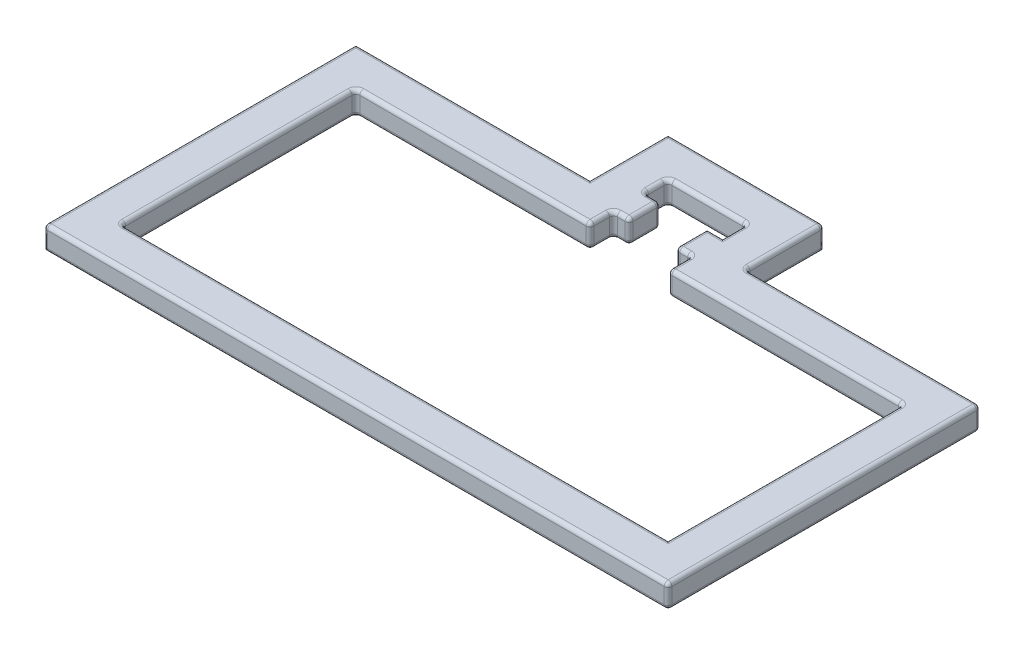
SolidWorks part; units mm, degrees
ref_plane "Front Plane" through (0, 0, 0) normal (0, 0, 1) x (1, 0, 0)
ref_plane "Top Plane" through (0, 0, 0) normal (0, 1, 0) x (1, 0, 0)
ref_plane "Right Plane" through (0, 0, 0) normal (1, 0, 0) x (0, 0, -1)
sketch "Sketch1" plane through (0, 0, 0) normal (0, 1, 0) x (1, 0, 0)
  line L1 (-84.8117, 120.1282) -> (-4.8117, 120.1282)
  line L2 (-84.8117, 120.1282) -> (-84.8117, 80.1282)
  line L3 (-84.8117, 80.1282) -> (-4.8117, 80.1282)
  line L4 (-4.8117, 120.1282) -> (-4.8117, 80.1282)
  line L5 (-79.8117, 115.1282) -> (-9.8117, 115.1282)
  line L6 (-79.8117, 115.1282) -> (-79.8117, 85.1282)
  line L7 (-79.8117, 85.1282) -> (-9.8117, 85.1282)
  line L8 (-9.8117, 115.1282) -> (-9.8117, 85.1282)
  line L17 (-49.8117, 125.1282) -> (-39.8117, 125.1282)
  line L18 (-54.8117, 130.1282) -> (-34.8117, 130.1282)
  line L19 (-54.8117, 130.1282) -> (-54.8117, 120.1282)
  line L20 (-54.8117, 120.1282) -> (-34.8117, 120.1282)
  line L21 (-34.8117, 130.1282) -> (-34.8117, 120.1282)
  line L22 (-49.8117, 125.1282) -> (-49.8117, 115.1282)
  line L23 (-49.8117, 115.1282) -> (-39.8117, 115.1282)
  line L24 (-39.8117, 125.1282) -> (-39.8117, 115.1282)
  line L25 (-49.8117, 118.1282) -> (-47.8117, 118.1282)
  line L26 (-49.8117, 118.1282) -> (-49.8117, 122.1282)
  line L27 (-49.8117, 122.1282) -> (-47.8117, 122.1282)
  line L28 (-47.8117, 118.1282) -> (-47.8117, 122.1282)
  line L29 (-39.8117, 118.1282) -> (-41.8117, 118.1282)
  line L30 (-39.8117, 118.1282) -> (-39.8117, 122.1282)
  line L31 (-39.8117, 122.1282) -> (-41.8117, 122.1282)
  line L32 (-41.8117, 118.1282) -> (-41.8117, 122.1282)
  dimension "D1" = 80
  dimension "D2" = 40
  dimension "D3" = 5
  dimension "D4" = 5
  dimension "D5" = 5
  dimension "D6" = 5
  dimension "D7" = 20
  dimension "D8" = 10
  dimension "D9" = 5
  dimension "D10" = 5
  dimension "D11" = 30
  dimension "D12" = 10
  dimension "D13" = 4
  dimension "D14" = 2
  dimension "D15" = 3
  dimension "D16" = 2
  dimension "D17" = 4
  dimension "D18" = 3
extrude "Boss-Extrude1" add sketch "Sketch1" along normal blind 3 contours L1 L24 L5 L8 L7 L6 L22 L2 L3 L4 | L17 L24 L1 L21 L18 L19 L22 | L27 L28 L25 L26 | L31 L32 L29 L30
fillet "Fillet1" radius 0.5 60 edges at (-39.8117, 0, -116.6282) (-19.8117, 0, -120.1282) (-39.8117, 0, -123.6282) (-9.8117, 0, -100.1282) (-44.8117, 0, -85.1282) (-48.8117, 0, -122.1282) (-40.8117, 0, -118.1282) (-40.8117, 3, -122.1282) (-41.8117, 3, -120.1282) (-40.8117, 3, -118.1282) (-41.8117, 1.5, -118.1282) (-47.8117, 0, -120.1282) (-48.8117, 0, -118.1282) (-48.8117, 3, -122.1282) (-47.8117, 3, -120.1282) (-48.8117, 3, -118.1282) (-47.8117, 1.5, -122.1282) (-47.8117, 1.5, -118.1282) (-34.8117, 0, -125.1282) (-44.8117, 0, -80.1282) (-4.8117, 0, -100.1282) (-44.8117, 0, -125.1282) (-24.8117, 0, -115.1282) (-79.8117, 0, -100.1282) (-64.8117, 0, -115.1282) (-49.8117, 0, -116.6282) (-49.8117, 0, -123.6282) (-19.8117, 3, -120.1282) (-34.8117, 3, -125.1282) (-44.8117, 3, -130.1282) (-54.8117, 3, -125.1282) (-69.8117, 3, -120.1282) (-84.8117, 3, -100.1282) (-44.8117, 3, -80.1282) (-4.8117, 3, -100.1282) (-44.8117, 3, -125.1282) (-39.8117, 3, -116.6282) (-39.8117, 3, -123.6282) (-24.8117, 3, -115.1282) (-9.8117, 3, -100.1282) (-44.8117, 3, -85.1282) (-79.8117, 3, -100.1282) (-64.8117, 3, -115.1282) (-49.8117, 3, -116.6282) (-49.8117, 3, -123.6282) (-4.8117, 1.5, -120.1282) (-4.8117, 1.5, -80.1282) (-84.8117, 1.5, -80.1282) (-34.8117, 1.5, -130.1282) (-34.8117, 1.5, -120.1282) (-49.8117, 1.5, -125.1282) (-49.8117, 1.5, -115.1282) (-79.8117, 1.5, -115.1282) (-79.8117, 1.5, -85.1282) (-9.8117, 1.5, -115.1282) (-39.8117, 1.5, -115.1282) (-39.8117, 1.5, -125.1282) (-49.8117, 1.5, -122.1282) (-49.8117, 1.5, -118.1282) (-39.8117, 1.5, -118.1282)
equation "\"ScannerWidth\" = 80"
equation "\"ScannerLength\" = 40"
equation "\"SpineLength\" = 10"
equation "\"ScannerThickness\" = 5"
equation "\"D1@Sketch1\"=\"ScannerWidth\""
equation "\"D2@Sketch1\"=\"ScannerLength\""
equation "\"D3@Sketch1\"=\"ScannerThickness\""
equation "\"D4@Sketch1\"=\"ScannerThickness\""
equation "\"D5@Sketch1\"=\"ScannerThickness\""
equation "\"ScannerHeight\" = 3"
equation "\"SpineWidth\" = 10"
equation "\"D7@Sketch1\"=\"ScannerThickness\"*2+\"SpineWidth\""
equation "\"D6@Sketch1\"= \"ScannerThickness\""
equation "\"D9@Sketch1\"=\"ScannerThickness\""
equation "\"D8@Sketch1\"=\"SpineWidth\""
equation "\"D10@Sketch1\"=\"ScannerThickness\""
equation "\"D11@Sketch1\"=(\"ScannerWidth\"-\"SpineWidth\"-\"ScannerThickness\"*2)/2"
equation "\"TrainWidth\" = 4"
equation "\"TrainLength\"= 2"
equation "\"D13@Sketch1\"= \"TrainWidth\""
equation "\"D14@Sketch1\"=\"TrainLength\""
equation "\"D15@Sketch1\"=(\"SpineLength\"-\"TrainWidth\")/2"
equation "\"D16@Sketch1\"=\"TrainLength\""
equation "\"D17@Sketch1\"=\"TrainWidth\""
equation "\"D18@Sketch1\"=(\"SpineLength\"-\"TrainWidth\")/2"
equation "\"D1@Boss-Extrude1\"=\"ScannerHeight\""
equation "\"D12@Sketch1\"=\"SpineLength\""
